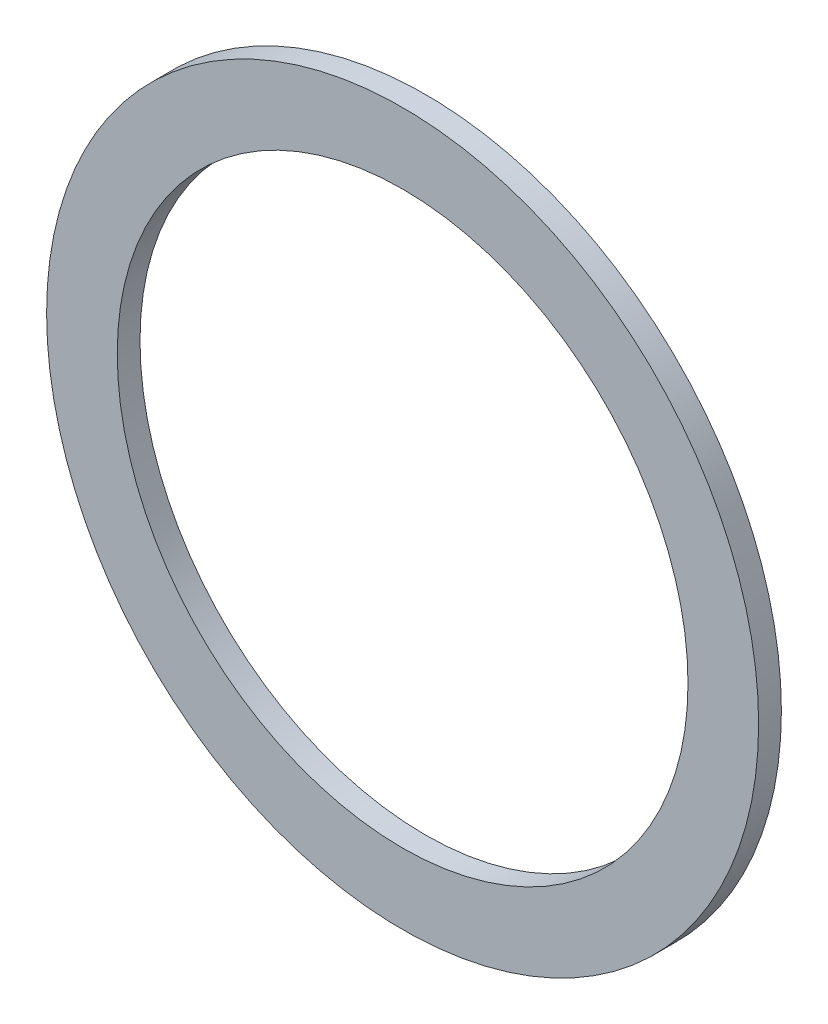
SolidWorks part; units mm, degrees
material "E-Glass Fiber"
ref_plane "Front Plane" through (0, 0, 0) normal (0, 0, 1) x (1, 0, 0)
ref_plane "Top Plane" through (0, 0, 0) normal (0, 1, 0) x (1, 0, 0)
ref_plane "Right Plane" through (0, 0, 0) normal (1, 0, 0) x (0, 0, -1)
sketch "Sketch1" plane through (0, 0, 0) normal (0, 0, 1) x (1, 0, 0)
  circle A0 centre (0, 0) radius 49.6697
  circle A1 centre (0, 0) radius 39.8145
  dimension "D1" = 99.3394
  dimension "D2" = 79.629
extrude "Boss-Extrude1" add sketch "Sketch1" along normal blind 3.175
